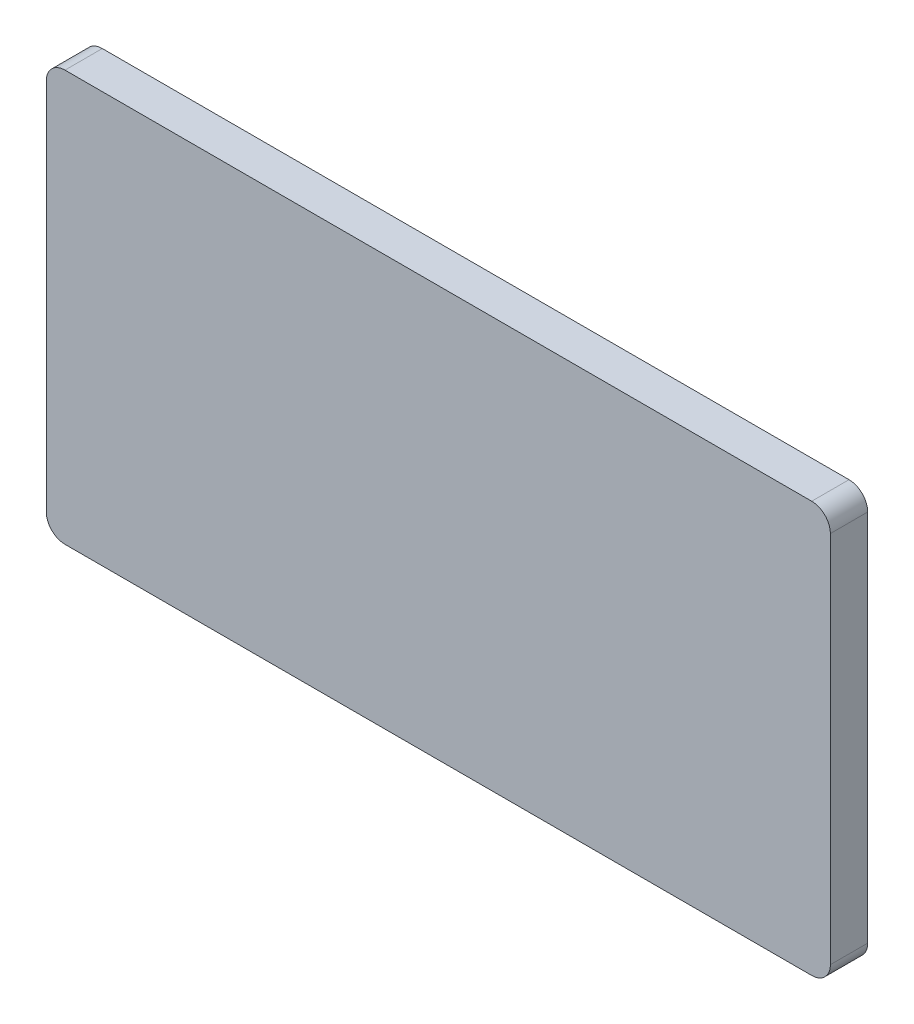
SolidWorks part; units mm, degrees
ref_plane "Alzado" through (0, 0, 0) normal (0, 0, 1) x (1, 0, 0)
ref_plane "Planta" through (0, 0, 0) normal (0, 1, 0) x (1, 0, 0)
ref_plane "Vista lateral" through (0, 0, 0) normal (1, 0, 0) x (0, 0, -1)
sketch "Croquis1" plane through (0, 0, 0) normal (0, 0, 1) x (1, 0, 0)
  line L1 (-41.3946, 28.1045) -> (58.6054, 28.1045)
  line L2 (-43.8946, 25.6045) -> (-43.8946, -24.3955)
  line L3 (-41.3946, -26.8955) -> (58.6054, -26.8955)
  line L4 (61.1054, 25.6045) -> (61.1054, -24.3955)
  arc A0 (-41.3946, 28.1045) -> (-43.8946, 25.6045) centre (-41.3946, 25.6045) ccw
  arc A1 (61.1054, 25.6045) -> (58.6054, 28.1045) centre (58.6054, 25.6045) ccw
  arc A2 (58.6054, -26.8955) -> (61.1054, -24.3955) centre (58.6054, -24.3955) ccw
  arc A3 (-43.8946, -24.3955) -> (-41.3946, -26.8955) centre (-41.3946, -24.3955) ccw
  dimension "D3" = 5
  dimension "D4" = 5
  dimension "D5" = 5
  dimension "D6" = 5
  dimension "D2" = 100
  dimension "D7" = 2.5
  dimension "D8" = 2.5
  dimension "D9" = 2.5
  dimension "D10" = 2.5
  dimension "D11" = 2.5
  dimension "D12" = 2.5
  dimension "D13" = 2.5
  dimension "D14" = 2.5
  dimension "D15" = 50
extrude "Saliente-Extruir1" add sketch "Croquis1" along normal blind 5
